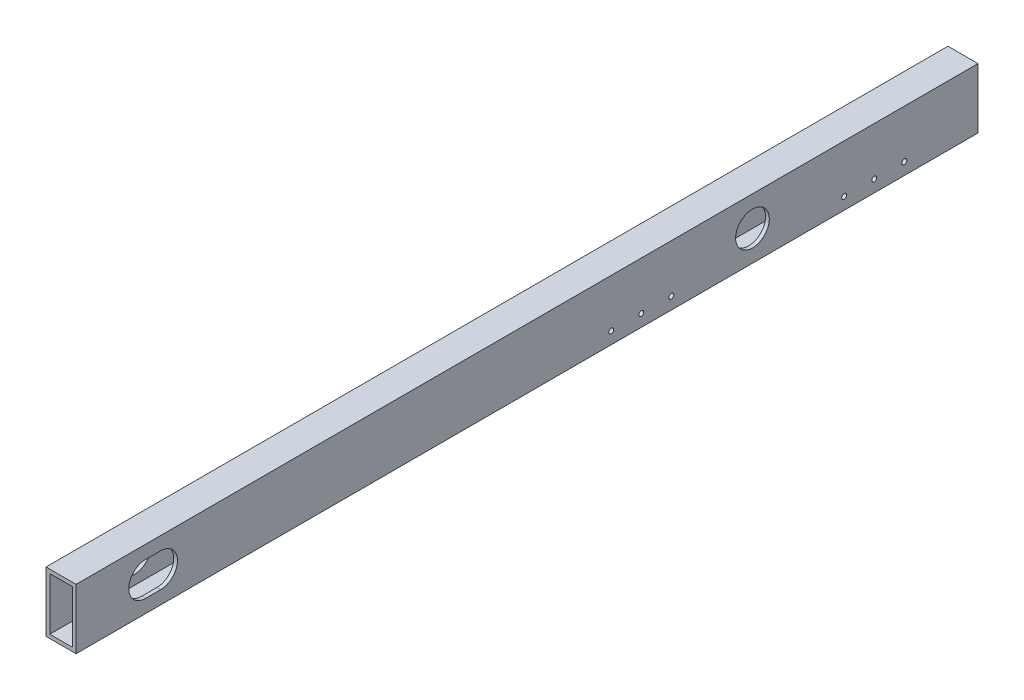
SolidWorks part; units mm, degrees
material "6061 Alloy"
ref_plane "Front Plane" through (0, 0, 0) normal (0, 0, 1) x (1, 0, 0)
ref_plane "Top Plane" through (0, 0, 0) normal (0, 1, 0) x (1, 0, 0)
ref_plane "Right Plane" through (0, 0, 0) normal (1, 0, 0) x (0, 0, -1)
sketch "Sketch1" plane through (0, 0, 0) normal (0, 0, 1) x (1, 0, 0)
  line L0 (0, 25.4) -> (0, 22.225) construction
  line L1 (-12.7, 25.4) -> (12.7, 25.4)
  line L2 (-12.7, 25.4) -> (-12.7, -25.4)
  line L3 (-12.7, -25.4) -> (12.7, -25.4)
  line L4 (12.7, 25.4) -> (12.7, -25.4)
  line L5 (-12.7, 25.4) -> (12.7, -25.4) construction
  line L6 (-12.7, -25.4) -> (12.7, 25.4) construction
  line L7 (-9.525, 22.225) -> (9.525, 22.225)
  line L8 (-9.525, 22.225) -> (-9.525, -22.225)
  line L9 (-9.525, -22.225) -> (9.525, -22.225)
  line L10 (9.525, 22.225) -> (9.525, -22.225)
  line L11 (9.525, 0) -> (12.7, 0) construction
  line L12 (-9.525, 0) -> (-12.7, 0) construction
  line L13 (0, -22.225) -> (0, -25.4) construction
  point P0 (0, 0)
  dimension "D1" = 50.8
  dimension "D2" = 25.4
  dimension "D3" = 3.175
extrude "Boss-Extrude1" add sketch "Sketch1" along normal blind 762
sketch "Sketch2" plane through (0, 25.4, 0) normal (0, 1, 0) x (1, 0, 0)
  line L0 (-26.9875, -190.549) -> (26.9875, -190.549) construction
  line L1 (-12.7, 0) -> (12.7, 0)
  line L2 (-12.7, 0) -> (-12.7, -762)
  line L3 (-12.7, -762) -> (12.7, -762)
  line L4 (12.7, 0) -> (12.7, -762)
  line L5 (-26.4963, -703.2466) -> (26.4963, -703.2466) construction
  line L6 (0, -703.2466) -> (0, -190.549) construction
  line L7 (0, 0) -> (0, -190.549) construction
  line L8 (-74.6125, -402.6047) -> (-73.6301, -528.6965) construction
  line L9 (-74.1213, -465.6506) -> (-23.8125, -465.6506) construction
  line L10 (-23.8125, -465.6506) -> (26.9875, -465.6506) construction
  dimension "D1" = 190.549
  dimension "D2" = 512.6976
  dimension "D3" = 126.0917
  dimension "D4" = 50.3088
  dimension "D5" = 50.8
  dimension "D6" = 53.975
  dimension "D7" = 52.9926
  dimension "D8" = 275.1016
ref_plane "Plane1" through (12.7, 0, 0) normal (1, 0, 0) x (0, 0, -1)
sketch "Sketch4" plane through (12.7, 0, 0) normal (1, 0, 0) x (0, 0, -1)
  line L0 (-690.548, 25.4) -> (-690.548, 0) construction
  line L1 (-703.2466, 25.4) -> (-190.549, 25.4) construction
  line L2 (-190.549, 25.4) -> (-190.549, 0) construction
  line L3 (0, 25.4) -> (-190.549, 25.4) construction
  line L4 (-190.549, 0) -> (0, 0) construction
  line L5 (0, -25.4) -> (0, 25.4) construction
  line L6 (-190.549, 0) -> (-690.548, 0) construction
  line L7 (-690.548, 0) -> (-703.248, 0) construction
  line L8 (-703.248, 0) -> (-703.248, 14.224) construction
  line L9 (-703.248, 14.224) -> (-690.548, 14.224)
  line L10 (-703.248, 0) -> (-703.248, -14.224) construction
  line L11 (-703.248, -14.224) -> (-690.548, -14.224)
  circle A1 centre (-190.549, 0) radius 14.224
  arc A2 (-703.248, 14.224) -> (-703.248, -14.224) centre (-703.248, 0) ccw
  arc A3 (-690.548, -14.224) -> (-690.548, 14.224) centre (-690.548, 0) ccw
  point P25 (-703.248, 0)
  dimension "D1" = 14.224
  dimension "D5" = 28.448
  dimension "D2" = 499.999
  dimension "D3" = 190.549
  dimension "D4" = 12.7
extrude "Cut-Extrude1" cut sketch "Sketch4" against normal up to surface (25.4 mm away) up to face at (-12.7, 0, 381)
sketch "Sketch5" plane through (0, -25.4, 0) normal (0, -1, 0) x (1, 0, 0)
  line L0 (-12.7, 0) -> (-12.7, 762) construction
  line L2 (0, 264.16) -> (0, 328.0394) construction
  line L4 (-12.7, 264.16) -> (12.7, 264.16) construction
  line L5 (12.7, 0) -> (12.7, 762) construction
  line L6 (2.54, 264.16) -> (2.54, 340.36) construction
  line L7 (0, 703.2466) -> (0, 190.549) construction
  circle A0 centre (2.54, 264.16) radius 2.0955
  circle A1 centre (2.54, 289.56) radius 2.0955
  circle A2 centre (2.54, 314.96) radius 2.0955
  circle A3 centre (-2.54, 264.16) radius 2.0955
  circle A4 centre (-2.54, 289.56) radius 2.0955
  circle A5 centre (-2.54, 314.96) radius 2.0955
  dimension "D4" = 4.191
  dimension "D1" = 264.16
  dimension "D3" = 76.2
  dimension "D6" = 10.16
  dimension "D5" = 3
extrude "Cut-Extrude2" cut sketch "Sketch5" against normal up to surface (3.175 mm away) up to face at (0, -22.225, 381)
sketch "Sketch7" plane through (12.7, 0, 0) normal (1, 0, 0) x (0, 0, -1)
  line L0 (0, -15.24) -> (-25.4, -15.24) construction
  line L1 (0, -25.4) -> (0, 25.4) construction
  line L2 (-259.08, -15.24) -> (-297.18, -15.24) construction
  line L3 (-762, -25.4) -> (0, -25.4) construction
  line L4 (-149.86, -15.24) -> (-25.4, -15.24) construction
  line L5 (-149.86, -15.24) -> (-259.08, -15.24) construction
  circle A0 centre (-259.08, -15.24) radius 2.0955
  circle A1 centre (-284.48, -15.24) radius 2.0955
  circle A2 centre (-309.88, -15.24) radius 2.0955
  circle A3 centre (-87.63, -15.24) radius 2.0955
  circle A4 centre (-62.23, -15.24) radius 2.0955
  circle A5 centre (-113.03, -15.24) radius 2.0955
  dimension "D3" = 4.191
  dimension "D1" = 259.08
  dimension "D2" = 38.1
  dimension "D5" = 10.16
  dimension "D6" = 124.46
  dimension "D7" = 25.4
  dimension "D4" = 3
  dimension "D8" = 2
  dimension "D9" = 2
extrude "Cut-Extrude3" cut sketch "Sketch7" against normal up to surface (25.4 mm away) up to face at (-12.7, 0, 176.325)
